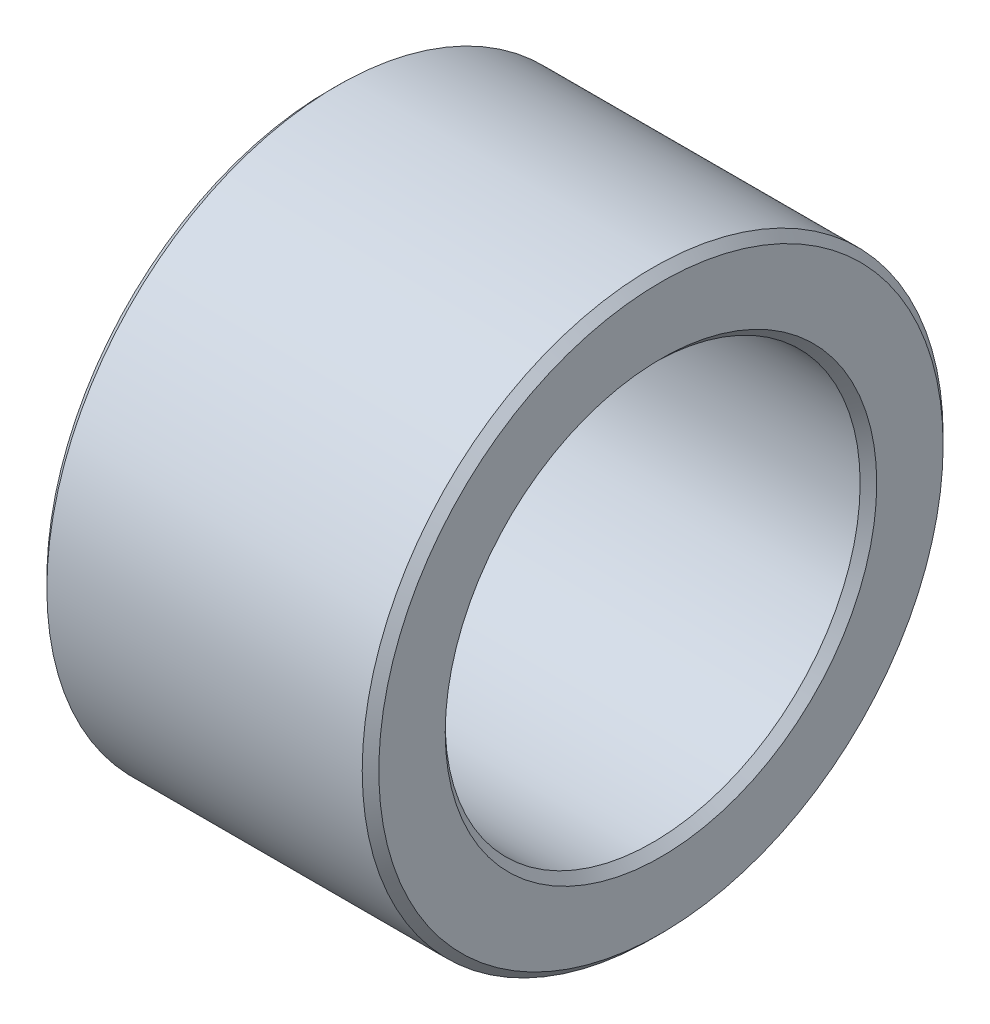
SolidWorks part; units mm, degrees
other "标注1"
sketch "草图2" plane through (0, 3.5, -3.5) normal (-0.2968, 0.4965, -0.8157) x (0.5922, -0.5744, -0.5651)
other "标注2"
sketch "草图3" plane through (0, 3.5, -3.5) normal (-0.2968, 0.4965, -0.8157) x (0.5922, -0.5744, -0.5651)
material "AISI 304"
ref_plane "前视基准面" through (0, 0, 0) normal (1, 0, 0) x (0, 1, 0)
ref_plane "上视基准面" through (0, 0, 0) normal (0, 0, 1) x (0, 1, 0)
ref_plane "右视基准面" through (0, 0, 0) normal (0, 1, 0) x (-1, 0, 0)
other "Configuration Table"
sketch "草图1" plane through (0, 0, 0) normal (1, 0, 0) x (0, 1, 0)
  circle A0 centre (0, 0) radius 3.5
  circle A1 centre (0, 0) radius 2.5
  dimension "D1" = 7
  dimension "D2" = 5
extrude "凸台-拉伸1" add sketch "草图1" along normal blind 4
chamfer "倒角1" distance 0.1 angle 45 4 edges at (4, 0, -2.5) (0, 0, -2.5) (0, 0, -3.5) (4, 0, -3.5)
